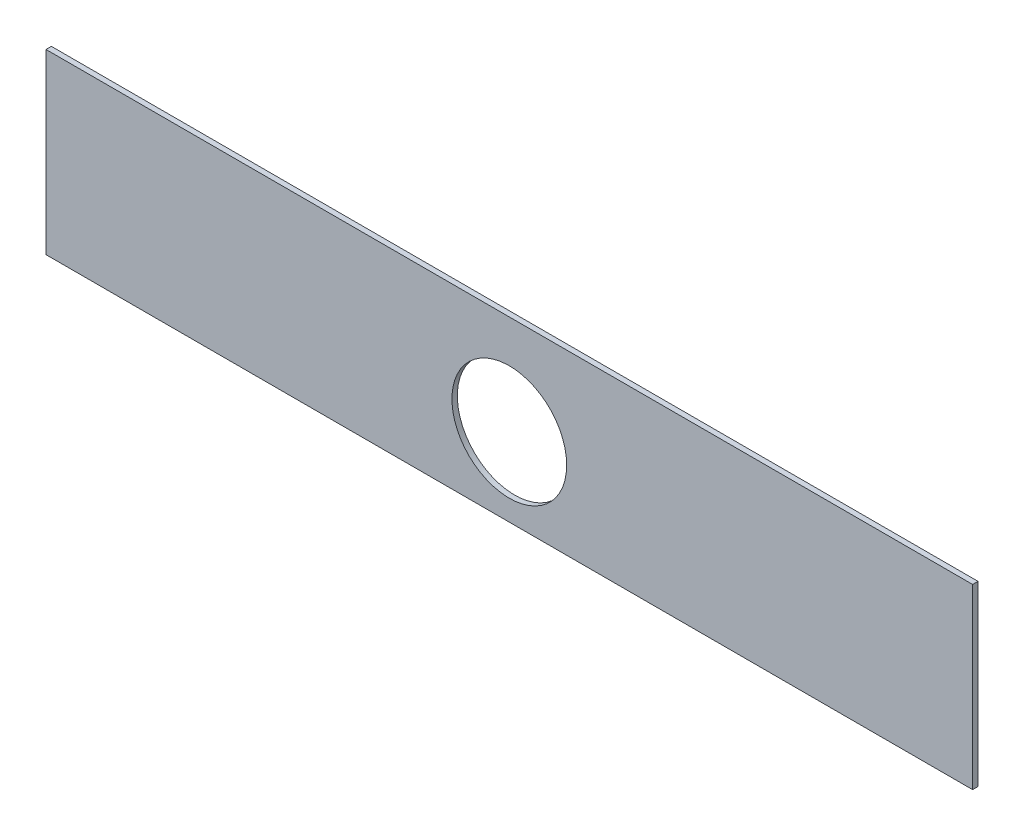
SolidWorks part; units mm, degrees
ref_plane "Front Plane" through (0, 0, 0) normal (0, 0, 1) x (1, 0, 0)
ref_plane "Top Plane" through (0, 0, 0) normal (0, 1, 0) x (1, 0, 0)
ref_plane "Right Plane" through (0, 0, 0) normal (1, 0, 0) x (0, 0, -1)
sketch "Sketch1" plane through (0, 0, 0) normal (0, 0, 1) x (1, 0, 0)
  line L0 (0, 0) -> (0, 33)
  line L1 (0, 33) -> (172.05, 33)
  line L2 (172.05, 33) -> (172.05, 0)
  line L3 (172.05, 0) -> (0, 0)
  line L4 (86.025, 0) -> (86.025, 14.5) construction
  circle A0 centre (86.025, 14.5) radius 10.65
  dimension "D1" = 33
  dimension "D2" = 172.05
  dimension "D3" = 14.5
extrude "Boss-Extrude1" add sketch "Sketch1" along normal blind 1
